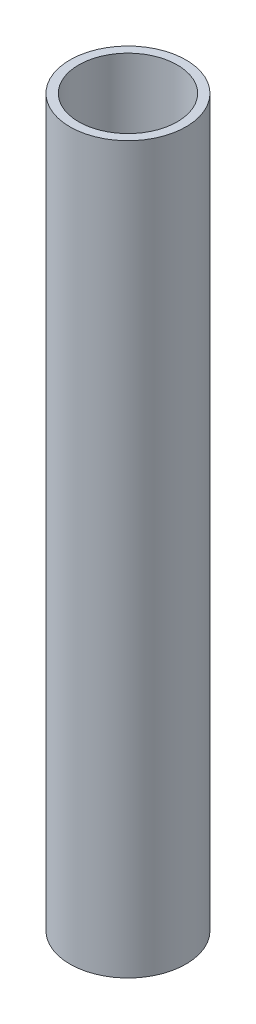
SolidWorks part; units mm, degrees
ref_plane "前视基准面" through (0, 0, 0) normal (0, 0, 1) x (1, 0, 0)
ref_plane "上视基准面" through (0, 0, 0) normal (0, 1, 0) x (1, 0, 0)
ref_plane "右视基准面" through (0, 0, 0) normal (1, 0, 0) x (0, 0, -1)
other "Configuration Table"
sketch "草图1" plane through (0, 0, 0) normal (0, 1, 0) x (1, 0, 0)
  circle A14 centre (0, 0) radius 16
  circle A15 centre (0, 0) radius 13.6
  dimension "D1" = 32
  dimension "D2" = 2.4
extrude "凸台-拉伸1" add sketch "草图1" along normal blind 200
